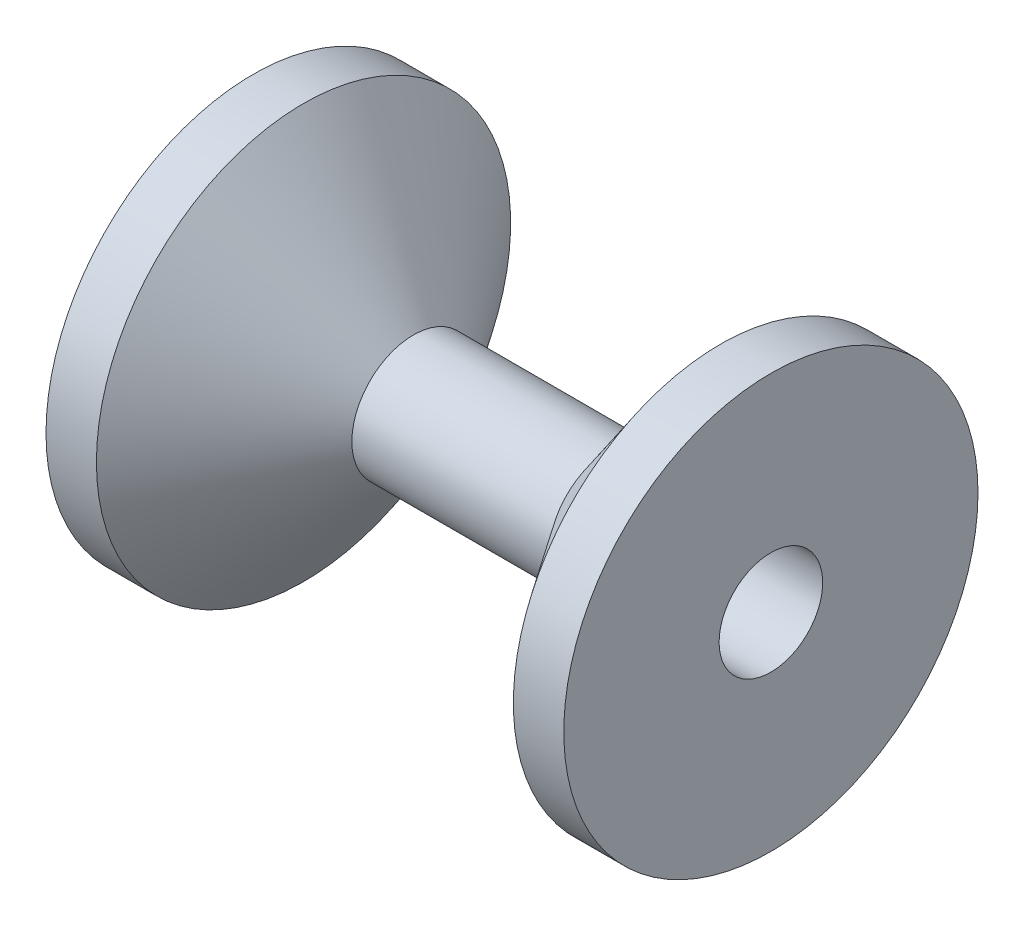
SolidWorks part; units mm, degrees
ref_plane "Front Plane" through (0, 0, 0) normal (0, 0, 1) x (1, 0, 0)
ref_plane "Top Plane" through (0, 0, 0) normal (0, 1, 0) x (1, 0, 0)
ref_plane "Right Plane" through (0, 0, 0) normal (1, 0, 0) x (0, 0, -1)
sketch "Sketch1" plane through (0, 0, 0) normal (1, 0, 0) x (0, 0, -1)
  circle A0 centre (0, 0) radius 40
  dimension "D1" = 80
extrude "Boss-Extrude1" add sketch "Sketch1" along normal blind 100
sketch "Sketch2" plane through (0, 0, 0) normal (0, 1, 0) x (1, 0, 0)
  line L0 (9.7369, 40) -> (30.9751, 11.9064)
  line L1 (100, 40) -> (0, 40) construction
  line L2 (30.9751, 11.9064) -> (69.0249, 11.9064)
  line L3 (50, 11.9064) -> (50, 40) construction
  line L4 (100, 40) -> (0, 40) construction
  line L5 (90.2631, 40) -> (69.0249, 11.9064)
  line L6 (9.7369, 40) -> (90.2631, 40)
  line L7 (0, 0) -> (100, 0) construction
  line L8 (100, -40) -> (100, 40) construction
  point P15 (9.7369, 40)
  point P16 (32.0866, 7.9178)
  point P17 (34.6697, 7.0194)
revolve "Cut-Revolve1" cut sketch "Sketch2" angle 360 about L7
sketch "Sketch3" plane through (0, 0, 0) normal (-1, 0, 0) x (0, 0, 1)
  circle A0 centre (0, 0) radius 10
  dimension "D1" = 20
extrude "Cut-Extrude1" cut sketch "Sketch3" against normal through all
